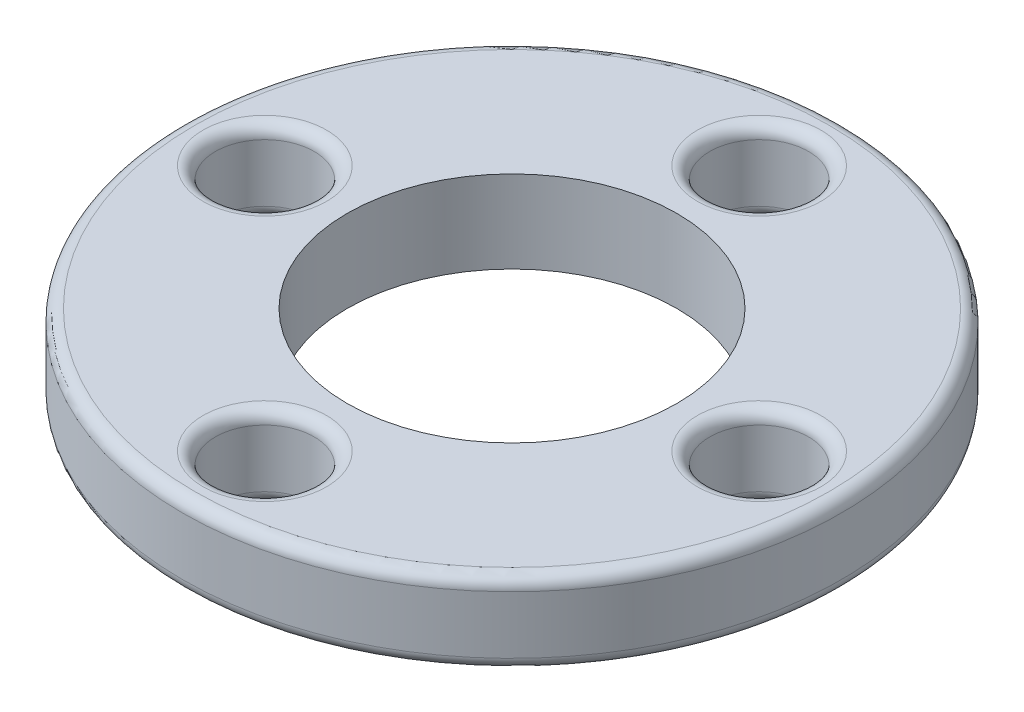
SolidWorks part; units mm, degrees
ref_plane "前视基准面" through (0, 0, 0) normal (0, 0, 1) x (1, 0, 0)
ref_plane "上视基准面" through (0, 0, 0) normal (0, 1, 0) x (1, 0, 0)
ref_plane "右视基准面" through (0, 0, 0) normal (1, 0, 0) x (0, 0, -1)
other "Configuration Table"
sketch "草图1" plane through (0, 0, 0) normal (0, 1, 0) x (1, 0, 0)
  line L0 (0, 14.8005) -> (0, 0) construction
  line L1 (0, 0) -> (11.7467, 0) construction
  circle A0 centre (0, 0) radius 8
  circle A1 centre (0, 0) radius 6 construction
  circle A2 centre (0, 6) radius 1.2
  circle A3 centre (0, 0) radius 4
  circle A4 centre (6, 0) radius 1.2
  circle A5 centre (0, -6) radius 1.2
  circle A6 centre (-6, 0) radius 1.2
  point P9 (0, 6)
  point P10 (0, 0)
  point P11 (0, 14.8005)
  point P18 (0, 0)
  point P19 (11.7467, 0)
  dimension "D1" = 12
  dimension "D2" = 2.4
  dimension "D3" = 16
  dimension "D4" = 8
  dimension "D5" = 4
extrude "凸台-拉伸1" add sketch "草图1" along normal blind 2
fillet "圆角1" radius 0.3 8 edges at (0, 0, 7.2) (0, 2, 7.2) (6, 0, 1.2) (6, 2, 1.2) (0, 0, -4.8) (0, 2, -4.8) (-6, 0, 1.2) (-6, 2, 1.2)
fillet "圆角2" radius 0.3 2 edges at (0, 0, 8) (0, 2, 8)
